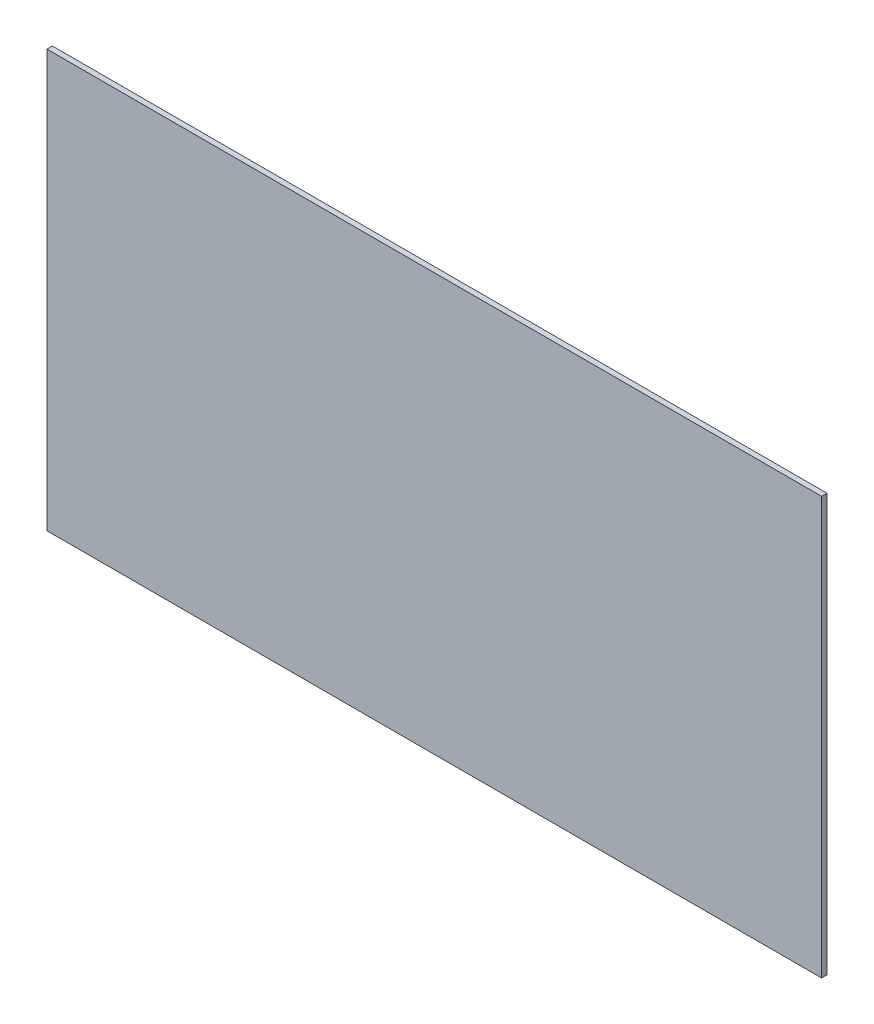
SolidWorks part; units mm, degrees
material "Maple"
ref_plane "Front Plane" through (0, 0, 0) normal (0, 0, 1) x (1, 0, 0)
ref_plane "Top Plane" through (0, 0, 0) normal (0, 1, 0) x (1, 0, 0)
ref_plane "Right Plane" through (0, 0, 0) normal (1, 0, 0) x (0, 0, -1)
sketch "Sketch1" plane through (0, 0, 0) normal (0, 0, 1) x (1, 0, 0)
  line L1 (0, 0) -> (1816.1, 0)
  line L2 (0, 0) -> (0, 977.9)
  line L3 (0, 977.9) -> (1816.1, 977.9)
  line L4 (1816.1, 0) -> (1816.1, 977.9)
  dimension "D1" = 1816.1
  dimension "D2" = 977.9
extrude "Boss-Extrude1" add sketch "Sketch1" along normal blind 12.7 contours L2 L3 L4 L1
